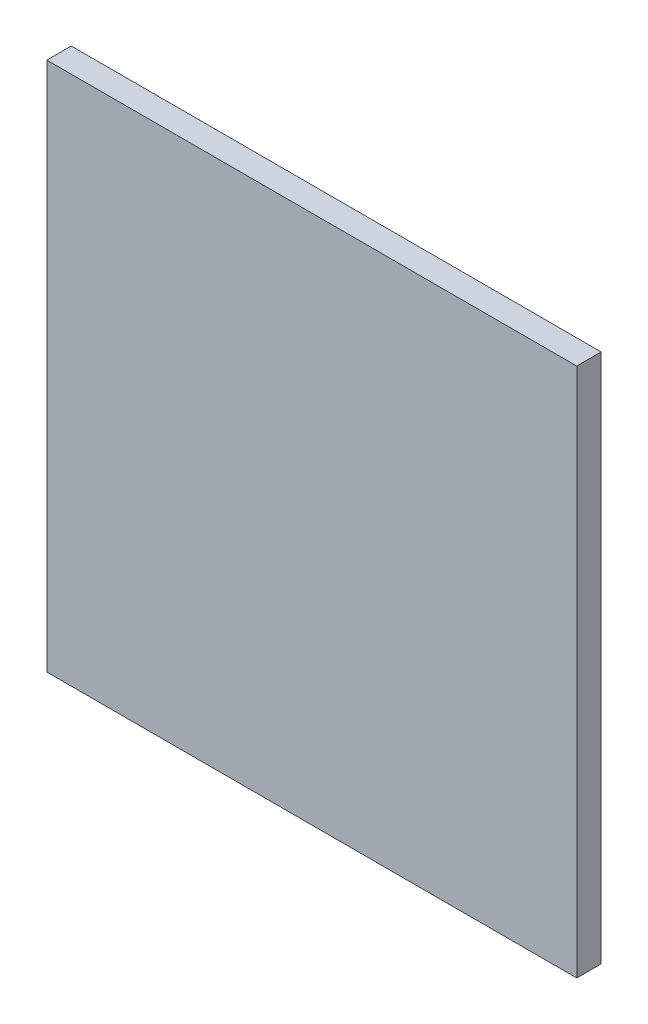
SolidWorks part; units mm, degrees
ref_plane "Front Plane" through (0, 0, 0) normal (0, 0, 1) x (1, 0, 0)
ref_plane "Top Plane" through (0, 0, 0) normal (0, 1, 0) x (1, 0, 0)
ref_plane "Right Plane" through (0, 0, 0) normal (1, 0, 0) x (0, 0, -1)
sketch "Sketch2" plane through (0, 0, 0) normal (0, 0, 1) x (1, 0, 0)
  line L1 (-35.585, -35.585) -> (35.585, -35.585)
  line L2 (-35.585, -35.585) -> (-35.585, 35.585)
  line L3 (-35.585, 35.585) -> (35.585, 35.585)
  line L4 (35.585, -35.585) -> (35.585, 35.585)
  line L5 (-35.585, -35.585) -> (35.585, 35.585) construction
  line L6 (-35.585, 35.585) -> (35.585, -35.585) construction
  point P0 (0, 0)
  dimension "D1" = 71.17
  dimension "D2" = 71.17
extrude "Boss-Extrude1" add sketch "Sketch2" along normal blind 3.28
